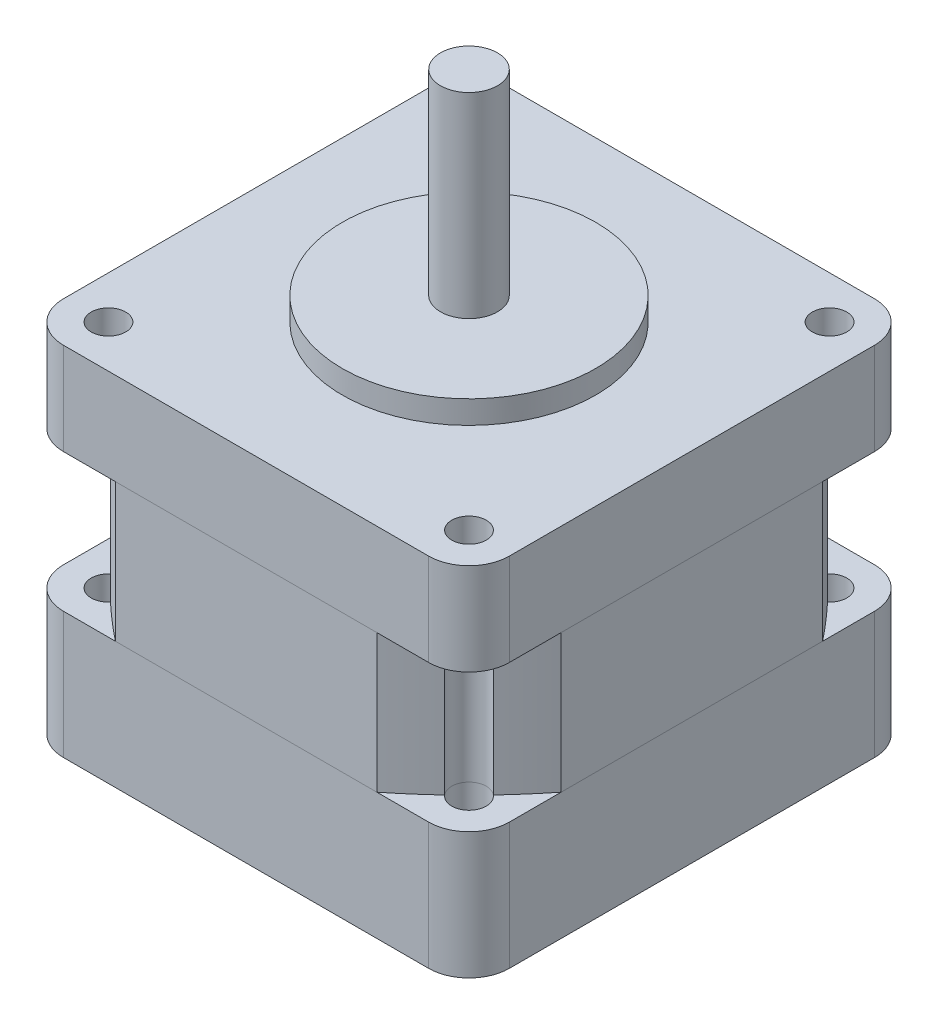
SolidWorks part; units mm, degrees
ref_plane "정면" through (0, 0, 0) normal (0, 0, 1) x (1, 0, 0)
ref_plane "윗면" through (0, 0, 0) normal (0, 1, 0) x (1, 0, 0)
ref_plane "우측면" through (0, 0, 0) normal (1, 0, 0) x (0, 0, -1)
sketch "스케치1" plane through (0, 0, 0) normal (0, 1, 0) x (1, 0, 0)
  line L1 (-19.35, -19.35) -> (19.35, -19.35)
  line L2 (-19.35, -19.35) -> (-19.35, 19.35)
  line L3 (-19.35, 19.35) -> (19.35, 19.35)
  line L4 (19.35, -19.35) -> (19.35, 19.35)
  line L5 (-19.35, -19.35) -> (19.35, 19.35) construction
  line L6 (-19.35, 19.35) -> (19.35, -19.35) construction
  point P0 (0, 0)
  dimension "D1" = 38.7
  dimension "D2" = 38.7
extrude "보스-돌출1" add sketch "스케치1" along normal blind 11
sketch "스케치2" plane through (0, 11, 0) normal (0, 1, 0) x (1, 0, 0)
  line L1 (-19.35, -19.35) -> (19.35, -19.35)
  line L2 (-19.35, -19.35) -> (-19.35, 19.35)
  line L3 (-19.35, 19.35) -> (19.35, 19.35)
  line L4 (19.35, -19.35) -> (19.35, 19.35)
  line L5 (-19.35, -19.35) -> (19.35, 19.35) construction
  line L6 (-19.35, 19.35) -> (19.35, -19.35) construction
  point P0 (0, 0)
extrude "보스-돌출2" add sketch "스케치2" along normal blind 12 separate body
sketch "스케치3" plane through (0, 23, 0) normal (0, 1, 0) x (1, 0, 0)
  line L1 (-19.35, -19.35) -> (19.35, -19.35)
  line L2 (-19.35, -19.35) -> (-19.35, 19.35)
  line L3 (-19.35, 19.35) -> (19.35, 19.35)
  line L4 (19.35, -19.35) -> (19.35, 19.35)
  line L5 (-19.35, -19.35) -> (19.35, 19.35) construction
  line L6 (-19.35, 19.35) -> (19.35, -19.35) construction
  point P0 (0, 0)
extrude "보스-돌출3" add sketch "스케치3" along normal blind 8 separate body
sketch "스케치4" plane through (0, 23, 0) normal (0, 1, 0) x (1, 0, 0)
  line L0 (-19.35, -19.35) -> (19.35, -19.35) construction
  line L1 (19.35, 19.35) -> (-19.35, 19.35) construction
  line L2 (19.35, -19.35) -> (19.35, 19.35) construction
  line L3 (19.35, 11.35) -> (19.35, 19.35)
  line L4 (19.35, 19.35) -> (11.35, 19.35)
  line L5 (-19.35, 19.35) -> (-19.35, -19.35) construction
  line L6 (19.35, -11.35) -> (19.35, -19.35)
  line L7 (19.35, -19.35) -> (11.35, -19.35)
  line L8 (-19.35, -11.35) -> (-19.35, -19.35)
  line L9 (-19.35, -19.35) -> (-11.35, -19.35)
  line L10 (-19.35, 11.35) -> (-19.35, 19.35)
  line L11 (-19.35, 19.35) -> (-11.35, 19.35)
  arc A0 (11.35, 19.35) -> (19.35, 11.35) centre (-19.35, -19.35) cw
  arc A1 (-11.35, 19.35) -> (-19.35, 11.35) centre (19.35, -19.35) ccw
  arc A2 (-19.35, -11.35) -> (-11.35, -19.35) centre (19.35, 19.35) ccw
  arc A3 (11.35, -19.35) -> (19.35, -11.35) centre (-19.35, 19.35) ccw
  dimension "D1" = 8
extrude "컷-돌출1" cut sketch "스케치4" against normal up to next (12 mm away)
fillet "필렛1" radius 3.5 4 edges at (-19.35, 27, 19.35) (19.35, 27, 19.35) (-19.35, 27, -19.35) (19.35, 27, -19.35)
fillet "필렛2" radius 3.5 4 edges at (-19.35, 5.5, -19.35) (19.35, 5.5, -19.35) (19.35, 5.5, 19.35) (-19.35, 5.5, 19.35)
sketch "스케치5" plane through (0, 31, 0) normal (0, 1, 0) x (1, 0, 0)
  line L1 (-15.65, -15.65) -> (15.65, -15.65) construction
  line L2 (-15.65, -15.65) -> (-15.65, 15.65) construction
  line L3 (-15.65, 15.65) -> (15.65, 15.65) construction
  line L4 (15.65, -15.65) -> (15.65, 15.65) construction
  line L5 (-15.65, -15.65) -> (15.65, 15.65) construction
  line L6 (-15.65, 15.65) -> (15.65, -15.65) construction
  circle A0 centre (15.65, 15.65) radius 1.5
  circle A1 centre (-15.65, 15.65) radius 1.5
  circle A2 centre (-15.65, -15.65) radius 1.5
  circle A3 centre (15.65, -15.65) radius 1.5
  point P0 (0, 0)
  dimension "D2" = 3
  dimension "D1" = 31.3
extrude "컷-돌출2" cut sketch "스케치5" against normal through all
sketch "스케치6" plane through (0, 31, 0) normal (0, 1, 0) x (1, 0, 0)
  circle A0 centre (0, 0) radius 11
extrude "보스-돌출4" add sketch "스케치6" along normal blind 2
sketch "스케치7" plane through (0, 33, 0) normal (0, 1, 0) x (1, 0, 0)
  circle A0 centre (0, 0) radius 2.475
  dimension "D1" = 4.95
extrude "보스-돌출5" add sketch "스케치7" along normal blind 17
